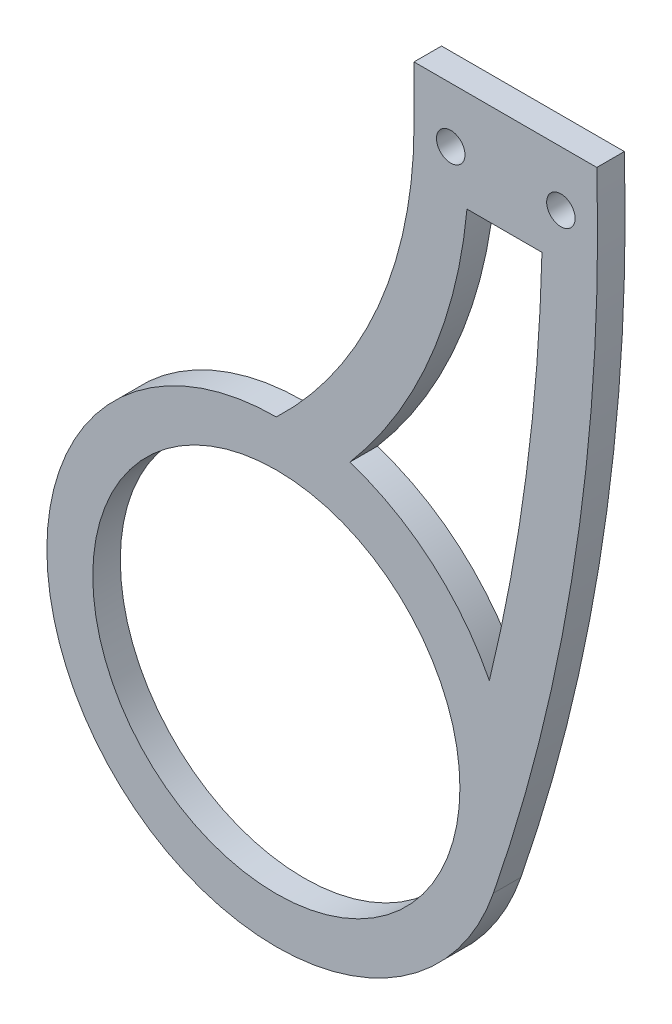
SolidWorks part; units mm, degrees
material "Thornel Mat VMA"
ref_plane "前视基准面" through (0, 0, 0) normal (0, 0, 1) x (1, 0, 0)
ref_plane "上视基准面" through (0, 0, 0) normal (0, 1, 0) x (1, 0, 0)
ref_plane "右视基准面" through (0, 0, 0) normal (1, 0, 0) x (0, 0, -1)
sketch "草图1" plane through (0, 0, 0) normal (0, 0, 1) x (1, 0, 0)
  line L0 (-4, 0) -> (-4, 6)
  line L1 (-4, 6) -> (16, 6)
  line L3 (6, 6) -> (6, -8.0386) construction
  line L4 (16, 6) -> (16, 0)
  line L6 (1.7694, -5) -> (9.9387, -5)
  circle A0 centre (0, 0) radius 1.55
  circle A1 centre (12, 0) radius 1.55
  circle A2 centre (-19, -60) radius 20
  arc A3 (-19, -35) -> (4.6486, -68.1081) centre (-19, -60) ccw
  arc A4 (-4, 0) -> (-19, -35) centre (-52.3333, 0) cw
  arc A5 (4.6486, -68.1081) -> (15.9143, 6) centre (-194, 0) ccw
  arc A6 (-10.9971, -35.2623) -> (1.7694, -5) centre (-52.3333, 0) ccw
  arc A7 (4.2059, -48.2745) -> (9.9387, -5) centre (-194, 0) ccw
  arc A8 (4.2059, -48.2745) -> (-10.9971, -35.2623) centre (-19, -60) ccw
  dimension "D2" = 3.1
  dimension "D3" = 60
  dimension "D8" = 40
  dimension "D9" = 5
  dimension "D10" = 6
  dimension "D11" = 6
  dimension "D13" = 6
  dimension "D1" = 12
  dimension "D4" = 6
  dimension "D5" = 4
  dimension "D6" = 4
  dimension "D7" = 25
  dimension "D12" = 5
extrude "凸台-拉伸1" add sketch "草图1" along normal blind 3
